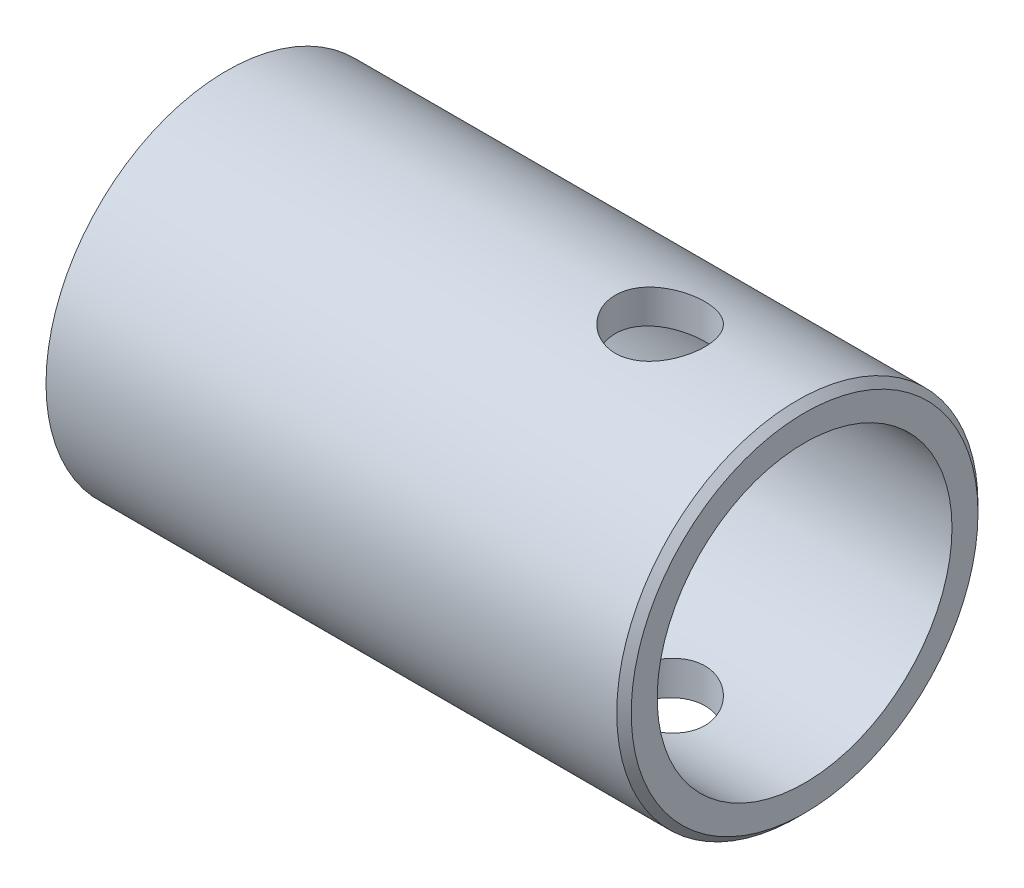
SolidWorks part; units mm, degrees
ref_plane "前视基准面" through (0, 0, 0) normal (0, 0, 1) x (1, 0, 0)
ref_plane "上视基准面" through (0, 0, 0) normal (0, 1, 0) x (1, 0, 0)
ref_plane "右视基准面" through (0, 0, 0) normal (1, 0, 0) x (0, 0, -1)
sketch "草图1" plane through (0, 0, 0) normal (1, 0, 0) x (0, 0, -1)
  circle A0 centre (0, 0) radius 10.2
  circle A1 centre (0, 0) radius 12.5
extrude "凸台-拉伸1" add sketch "草图1" along normal blind 30
sketch "草图2" plane through (0, 0, 0) normal (-1, 0, 0) x (0, 0, 1)
  circle A0 centre (0, 0) radius 12.5
extrude "凸台-拉伸2" add sketch "草图2" along normal blind 10
sketch "草图3" plane through (0, 0, 0) normal (0, 1, 0) x (1, 0, 0)
  line L0 (30, 0) -> (20, 0) construction
  line L1 (30, -12.5) -> (30, 12.5) construction
  circle A0 centre (20, 0) radius 3.1
extrude "切除-拉伸1" cut sketch "草图3" against normal mid plane 30 contours A0
chamfer "倒角1" distance 0.5 angle 45 1 edges at (30, 0, -12.5)
sketch "草图4" plane through (0, 0, 0) normal (1, 0, 0) x (0, 0, -1)
  circle A0 centre (0, 0) radius 10.2
extrude "切除-拉伸2" cut sketch "草图4" against normal blind 1
sketch "草图5" plane through (-10, 0, 0) normal (-1, 0, 0) x (0, 0, 1)
  circle A0 centre (0, 0) radius 9.53 construction
  circle A1 centre (9.53, 0) radius 1.05
  circle A2 centre (4.765, -8.2532) radius 1.05
  circle A3 centre (-4.765, -8.2532) radius 1.05
  circle A4 centre (-9.53, 0) radius 1.05
  circle A5 centre (-4.765, 8.2532) radius 1.05
  circle A6 centre (4.765, 8.2532) radius 1.05
  point P18 (0, 0)
  dimension "D1" = 6
extrude "切除-拉伸3" cut sketch "草图5" against normal blind 6
